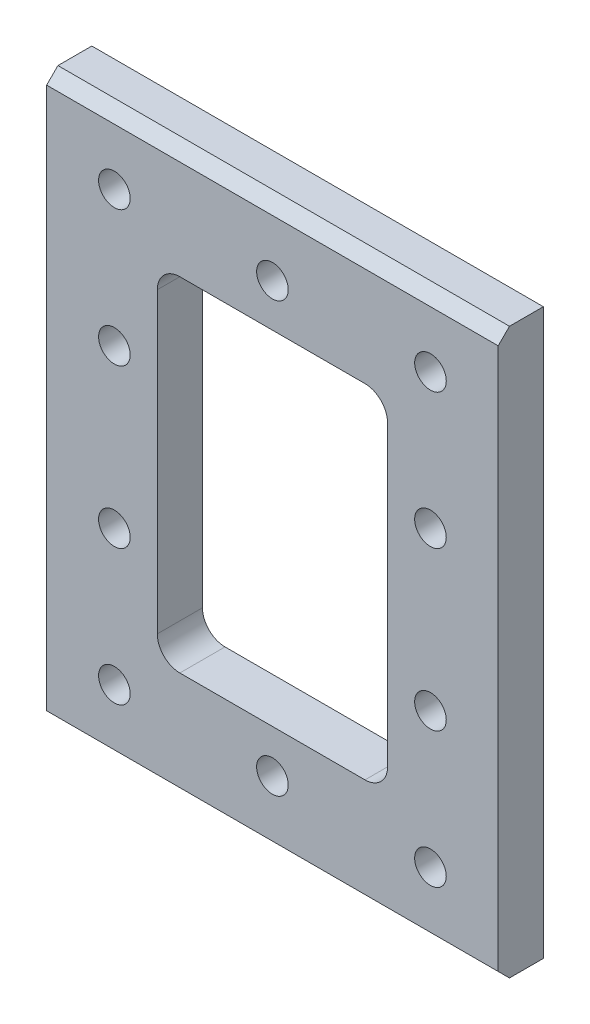
SolidWorks part; units mm, degrees
ref_plane "前视基准面" through (0, 0, 0) normal (0, 0, 1) x (1, 0, 0)
ref_plane "上视基准面" through (0, 0, 0) normal (0, 1, 0) x (1, 0, 0)
ref_plane "右视基准面" through (0, 0, 0) normal (1, 0, 0) x (0, 0, -1)
sketch "草图1" plane through (0, 0, 0) normal (0, 0, 1) x (1, 0, 0)
  line L1 (-100, 125) -> (100, 125)
  line L2 (-100, 125) -> (-100, -125)
  line L3 (-100, -125) -> (100, -125)
  line L4 (100, 125) -> (100, -125)
  line L5 (-100, 125) -> (100, -125) construction
  line L6 (-100, -125) -> (100, 125) construction
  point P0 (0, 0)
  dimension "D1" = 200
  dimension "D2" = 250
extrude "凸台-拉伸1" add sketch "草图1" along normal blind 20
sketch "草图2" plane through (0, 0, 20) normal (0, 0, 1) x (1, 0, 0)
  line L0 (0, 0) -> (-148.4114, 0) construction
  line L1 (-41, 76) -> (41, 76)
  line L2 (-51, 66) -> (-51, -66)
  line L3 (-41, -76) -> (41, -76)
  line L4 (51, 66) -> (51, -66)
  line L5 (-51, 76) -> (51, -76) construction
  line L6 (-51, -76) -> (51, 76) construction
  line L7 (100, 125) -> (-100, 125) construction
  line L8 (-100, 125) -> (-100, -125) construction
  arc A0 (-51, -66) -> (-41, -76) centre (-41, -66) ccw
  arc A1 (41, -76) -> (51, -66) centre (41, -66) ccw
  arc A2 (41, 76) -> (51, 66) centre (41, 66) cw
  arc A3 (-41, 76) -> (-51, 66) centre (-41, 66) ccw
  circle A4 centre (-70, 95) radius 7
  circle A5 centre (0, 95) radius 7
  circle A6 centre (70, 95) radius 7
  circle A7 centre (-70, 35) radius 7
  circle A8 centre (70, 35) radius 7
  circle A9 centre (-70, -35) radius 7
  circle A10 centre (0, -95) radius 7
  circle A11 centre (-70, -95) radius 7
  circle A12 centre (70, -35) radius 7
  circle A13 centre (70, -95) radius 7
  point P0 (0, 0)
  point P40 (0, 0)
  point P41 (0, 0)
  point P42 (0, 0)
  point P47 (0, 0)
  dimension "D3" = 10
  dimension "D4" = 30
  dimension "D5" = 60
  dimension "D6" = 14
  dimension "D7" = 14
  dimension "D8" = 14
  dimension "D9" = 14
  dimension "D10" = 14
  dimension "D11" = 70
  dimension "D12" = 70
  dimension "D13" = 30
  dimension "D1" = 152
  dimension "D2" = 102
extrude "切除-拉伸1" cut sketch "草图2" against normal up to next
chamfer "倒角1" distance 5 angle 45 2 edges at (0, -125, 20) (0, 125, 20)
